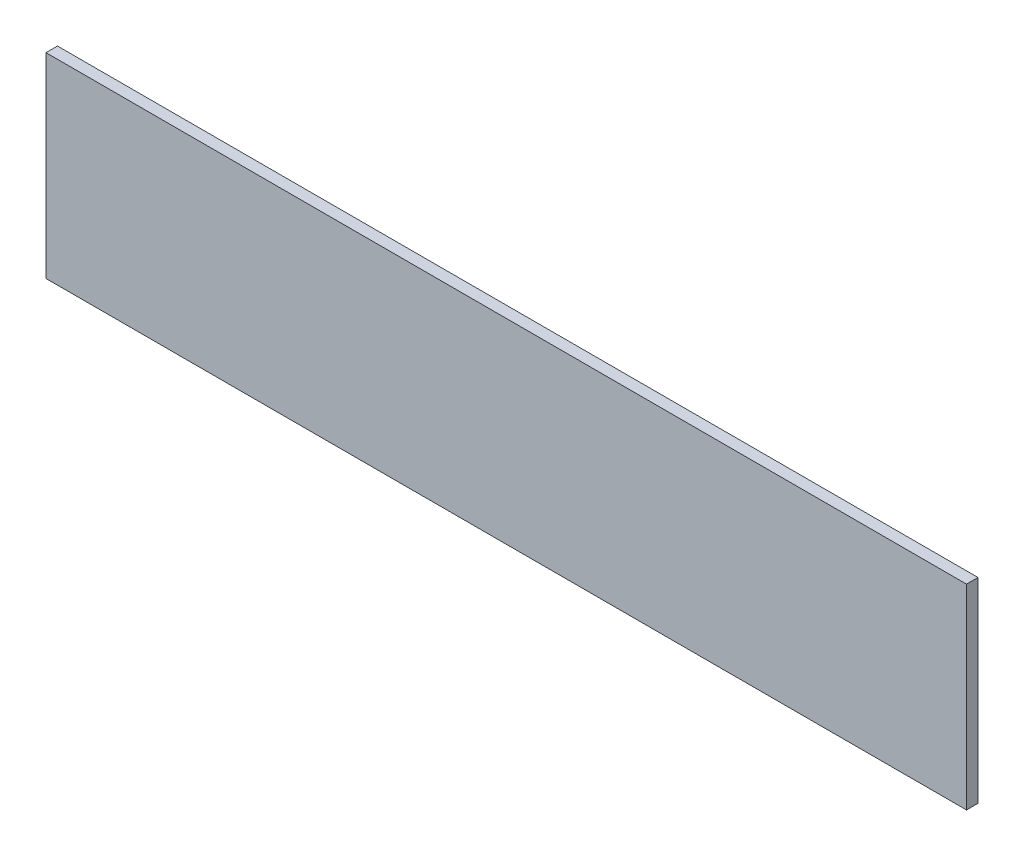
SolidWorks part; units mm, degrees
ref_plane "Ebene vorne" through (0, 0, 0) normal (0, 0, 1) x (1, 0, 0)
ref_plane "Ebene oben" through (0, 0, 0) normal (0, 1, 0) x (1, 0, 0)
ref_plane "Ebene rechts" through (0, 0, 0) normal (1, 0, 0) x (0, 0, -1)
sketch "Skizze1" plane through (0, 0, 0) normal (0, 0, 1) x (1, 0, 0)
  line L1 (0, 0) -> (400, 0)
  line L2 (0, 0) -> (0, 85)
  line L3 (0, 85) -> (400, 85)
  line L4 (400, 0) -> (400, 85)
  dimension "D1" = 85
  dimension "D2" = 400
extrude "Aufsatz-Linear austragen1" add sketch "Skizze1" along normal blind 5
